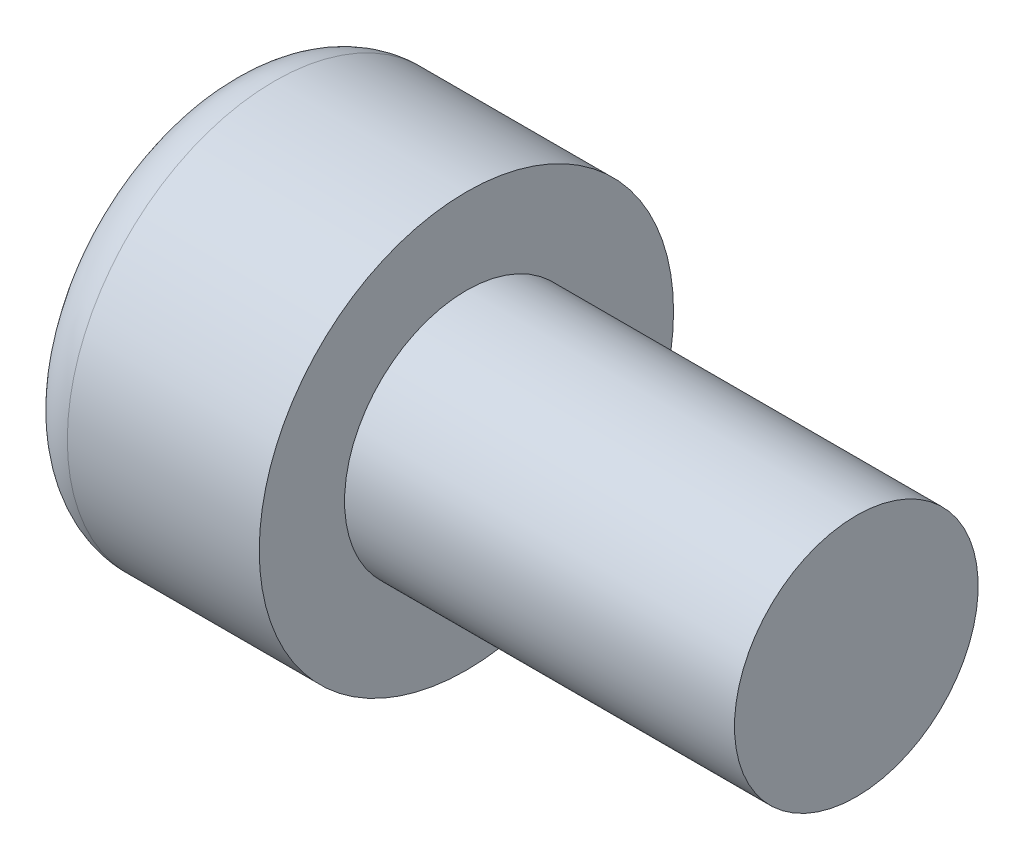
SolidWorks part; units mm, degrees
material "Plain Carbon Steel"
ref_plane "Front Plane" through (0, 0, 0) normal (0, 0, 1) x (1, 0, 0)
ref_plane "Top Plane" through (0, 0, 0) normal (0, 1, 0) x (1, 0, 0)
ref_plane "Right Plane" through (0, 0, 0) normal (1, 0, 0) x (0, 0, -1)
sketch "Sketch1" plane through (0, 0, 0) normal (0, 0, 1) x (1, 0, 0)
  line L0 (0, 0) -> (0, 3.1875)
  line L1 (1.0625, 4.25) -> (5, 4.25)
  line L2 (5, 4.25) -> (5, 2.5)
  line L3 (5, 2.5) -> (13, 2.5)
  line L4 (13, 2.5) -> (13, 0)
  line L5 (13, 0) -> (0, 0) construction
  line L6 (1.0625, 3.1875) -> (1.0625, 2.125) construction
  line L7 (1.0625, 2.125) -> (1.0625, 1.0625) construction
  line L8 (1.0625, 1.0625) -> (1.0625, 0) construction
  line L9 (1.0625, 4.25) -> (1.0625, 3.1875) construction
  line L10 (0, 0) -> (13, 0)
  arc A0 (0, 3.1875) -> (1.0625, 4.25) centre (1.0625, 3.1875) cw
  dimension "D1" = 5
  dimension "D2" = 8.5
  dimension "D3" = 5
  dimension "D4" = 8
revolve "Revolve1" add sketch "Sketch1" angle 360 about L10
sketch "Sketch2" plane through (0, 0, 0) normal (-1, 0, 0) x (0, 0, 1)
  line L1 (0, 2.3094) -> (-2, 1.1547)
  line L2 (-2, 1.1547) -> (-2, -1.1547)
  line L3 (-2, -1.1547) -> (0, -2.3094)
  line L4 (0, -2.3094) -> (2, -1.1547)
  line L5 (2, -1.1547) -> (2, 1.1547)
  line L6 (2, 1.1547) -> (0, 2.3094)
  circle A0 centre (0, 0) radius 2 construction
  dimension "D1" = 4
extrude "Cut-Extrude1" cut sketch "Sketch2" against normal blind 2.5
